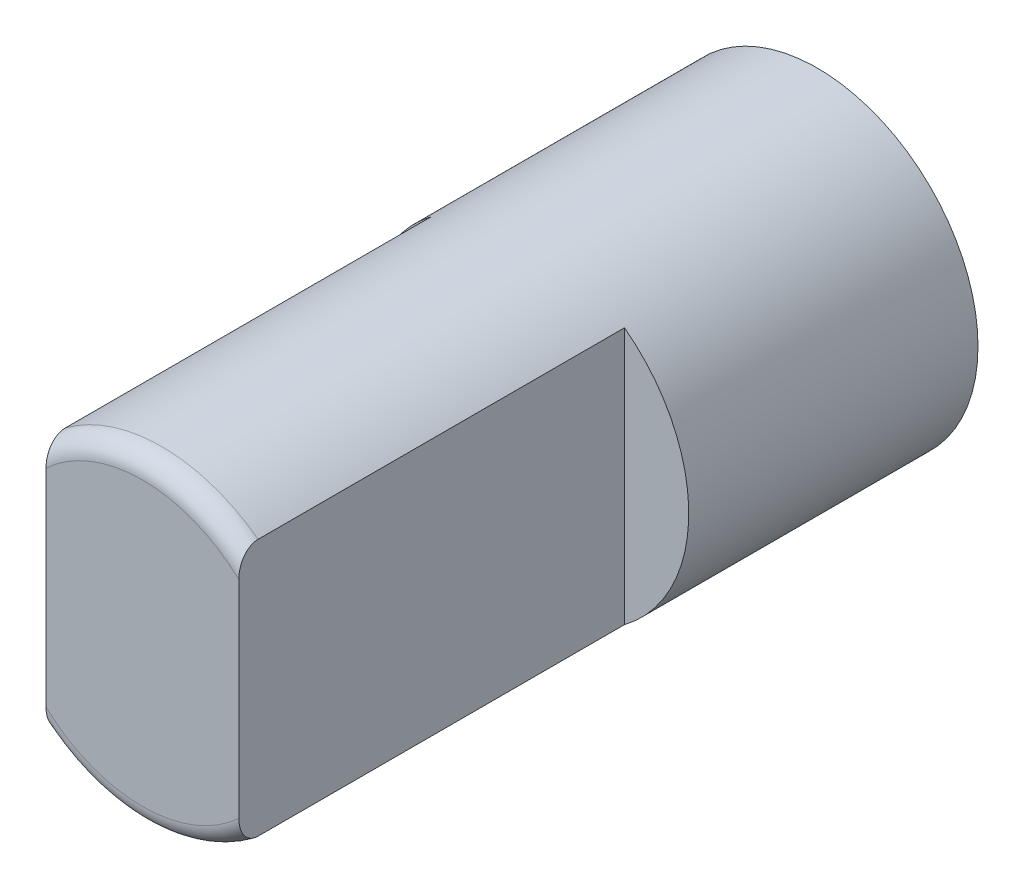
SolidWorks part; units mm, degrees
ref_plane "Plan de face" through (0, 0, 0) normal (0, 0, 1) x (1, 0, 0)
ref_plane "Plan de dessus" through (0, 0, 0) normal (0, 1, 0) x (1, 0, 0)
ref_plane "Plan de droite" through (0, 0, 0) normal (1, 0, 0) x (0, 0, -1)
sketch "Esquisse1" plane through (0, 0, 0) normal (0, 0, 1) x (1, 0, 0)
  circle A0 centre (0, 0) radius 2.5
  dimension "D1" = 5
extrude "Boss.-Extru.1" add sketch "Esquisse1" along normal blind 10.5
sketch "Esquisse3" plane through (0, 0, 10.5) normal (0, 0, 1) x (1, 0, 0)
  line L0 (0, 2.5) -> (0, -2.7613) construction
  line L2 (1.5, 2) -> (1.5, -2)
  line L4 (-1.5, -2) -> (-1.5, 2)
  circle A0 centre (0, 0) radius 2.5 construction
  arc A1 (-1.5, 2) -> (-1.5, -2) centre (0, 0) ccw
  arc A2 (1.5, -2) -> (1.5, 2) centre (0, 0) ccw
  point P9 (0, 2.5)
  dimension "D1" = 5
  dimension "D2" = 3
extrude "Enlèv. mat.-Extru.2" cut sketch "Esquisse3" against normal blind 6
fillet "Congé1" radius 0.3 2 edges at (0, 2.5, 10.5) (0, -2.5, 10.5)
